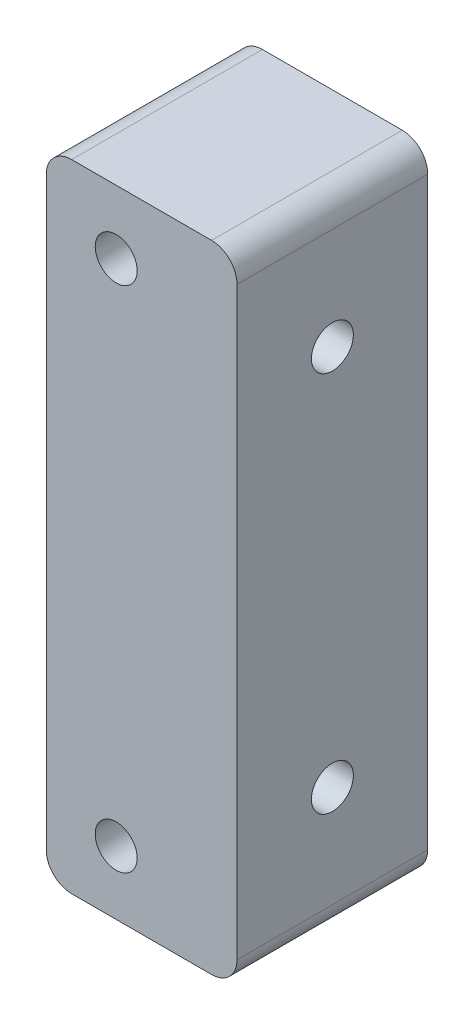
SolidWorks part; units mm, degrees
material "5052-H34"
ref_plane "正面" through (0, 0, 0) normal (0, 0, 1) x (1, 0, 0)
ref_plane "平面" through (0, 0, 0) normal (0, 1, 0) x (1, 0, 0)
ref_plane "右側面" through (0, 0, 0) normal (1, 0, 0) x (0, 0, -1)
sketch "ｽｹｯﾁ1" plane through (0, 0, 0) normal (0, 0, 1) x (1, 0, 0)
  line L0 (7.5, 50) -> (7.5, 0) construction
  line L1 (0, 0) -> (15, 0)
  line L2 (0, 0) -> (0, 50)
  line L3 (0, 50) -> (15, 50)
  line L4 (15, 0) -> (15, 50)
  line L5 (15, 25) -> (0, 25) construction
  circle A0 centre (5.5, 5) radius 1.65
  circle A1 centre (5.5, 45) radius 1.65
  dimension "D3" = 3.3
  dimension "D4" = 9.5
  dimension "D5" = 5
  dimension "D1" = 15
  dimension "D2" = 50
extrude "ﾎﾞｽ - 押し出し1" add sketch "ｽｹｯﾁ1" along normal blind 15
sketch "ｽｹｯﾁ2" plane through (0, 0, 0) normal (-1, 0, 0) x (0, 0, 1)
  line L0 (7.5, 50) -> (7.5, 0) construction
  line L1 (15, 50) -> (0, 50) construction
  line L2 (15, 0) -> (0, 0) construction
  line L3 (15, 25) -> (0, 25) construction
  line L4 (15, 50) -> (15, 0) construction
  line L5 (0, 50) -> (0, 0) construction
  circle A0 centre (7.5, 40) radius 1.65
  circle A1 centre (7.5, 10) radius 1.65
  dimension "D1" = 3.3
  dimension "D2" = 30
extrude "ｶｯﾄ - 押し出し1" cut sketch "ｽｹｯﾁ2" against normal up to surface (15 mm away) up to face at (15, 25, 7.5)
fillet "ﾌｨﾚｯﾄ1" radius 2 4 edges at (15, 0, 7.5) (0, 0, 7.5) (15, 50, 7.5) (0, 50, 7.5)
